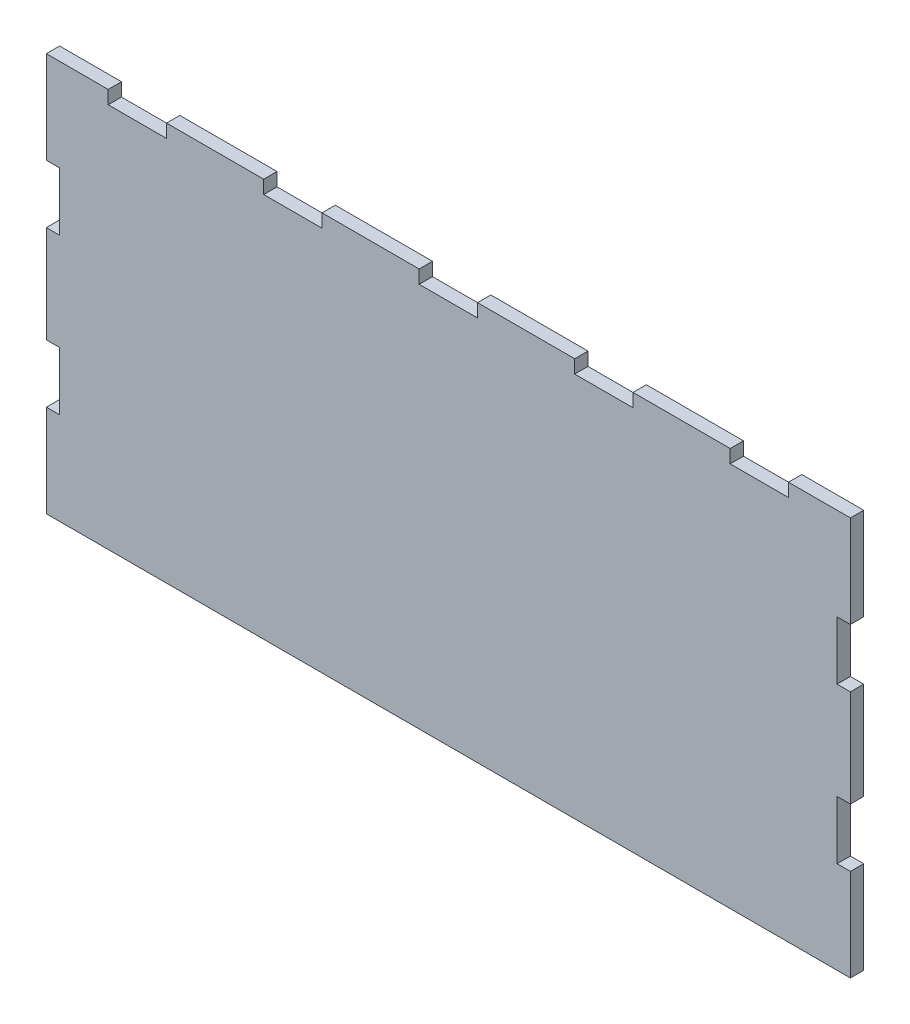
SolidWorks part; units mm, degrees
ref_plane "Front Plane" through (0, 0, 0) normal (0, 0, 1) x (1, 0, 0)
ref_plane "Top Plane" through (0, 0, 0) normal (0, 1, 0) x (1, 0, 0)
ref_plane "Right Plane" through (0, 0, 0) normal (1, 0, 0) x (0, 0, -1)
sketch "Sketch1" plane through (0, 0, 0) normal (0, 0, 1) x (1, 0, 0)
  line L1 (-131.3434, -65.0875) -> (131.3434, -65.0875)
  line L2 (-131.3434, -65.0875) -> (-131.3434, 65.0875)
  line L3 (-131.3434, 65.0875) -> (131.3434, 65.0875)
  line L4 (131.3434, -65.0875) -> (131.3434, 65.0875)
  line L5 (-131.3434, -65.0875) -> (131.3434, 65.0875) construction
  line L6 (-131.3434, 65.0875) -> (131.3434, -65.0875) construction
  point P0 (0, 0)
  dimension "D1" = 262.6868
  dimension "D2" = 130.175
extrude "Boss-Extrude1" add sketch "Sketch1" along normal blind 4.3434
sketch "Sketch2" plane through (0, 0, 4.3434) normal (0, 0, 1) x (1, 0, 0)
  line L2 (-60.325, 60.7441) -> (-41.275, 60.7441)
  line L3 (-60.325, 60.7441) -> (-60.325, 69.4309)
  line L4 (-60.325, 69.4309) -> (-41.275, 69.4309)
  line L5 (-41.275, 60.7441) -> (-41.275, 69.4309)
  line L6 (-60.325, 60.7441) -> (-41.275, 69.4309) construction
  line L7 (131.3434, 65.0875) -> (-131.3434, 65.0875) construction
  line L8 (-9.525, 60.7441) -> (9.525, 60.7441)
  line L9 (-9.525, 60.7441) -> (-9.525, 69.4309)
  line L10 (-9.525, 69.4309) -> (9.525, 69.4309)
  line L11 (9.525, 60.7441) -> (9.525, 69.4309)
  line L12 (-9.525, 60.7441) -> (9.525, 69.4309) construction
  line L13 (-9.525, 69.4309) -> (9.525, 60.7441) construction
  line L14 (41.275, 69.4309) -> (60.325, 69.4309)
  line L15 (60.325, 60.7441) -> (60.325, 69.4309)
  line L16 (41.275, 60.7441) -> (60.325, 60.7441)
  line L17 (41.275, 60.7441) -> (41.275, 69.4309)
  line L18 (92.075, 69.4309) -> (111.125, 69.4309)
  line L19 (111.125, 60.7441) -> (111.125, 69.4309)
  line L20 (92.075, 60.7441) -> (111.125, 60.7441)
  line L21 (92.075, 60.7441) -> (92.075, 69.4309)
  line L22 (-60.325, 69.4309) -> (-41.275, 60.7441) construction
  line L23 (-111.125, 60.7441) -> (-92.075, 60.7441)
  line L24 (-111.125, 60.7441) -> (-111.125, 69.4309)
  line L25 (-111.125, 69.4309) -> (-92.075, 69.4309)
  line L26 (-92.075, 60.7441) -> (-92.075, 69.4309)
  line L27 (-111.125, 60.7441) -> (-92.075, 69.4309) construction
  line L28 (-111.125, 69.4309) -> (-92.075, 60.7441) construction
  line L29 (-131.3434, 65.0875) -> (-131.3434, -65.0875) construction
  point P1 (-50.8, 65.0875)
  point P7 (0, 65.0875)
  point P15 (-101.6, 65.0875)
  point P32 (97.2566, 69.4309)
  dimension "D1" = 3
  dimension "D2" = 8.6868
  dimension "D3" = 19.05
  dimension "D4" = 121.8184
  dimension "D7" = 3
extrude "Cut-Extrude1" cut sketch "Sketch2" against normal through all
sketch "Sketch3" plane through (0, 0, 4.3434) normal (0, 0, 1) x (1, 0, 0)
  line L0 (-131.3434, 65.0875) -> (-131.3434, -65.0875) construction
  line L1 (-135.6868, -34.925) -> (-127, -34.925)
  line L2 (-135.6868, -34.925) -> (-135.6868, -15.875)
  line L3 (-135.6868, -15.875) -> (-127, -15.875)
  line L4 (-127, -34.925) -> (-127, -15.875)
  line L5 (-135.6868, -34.925) -> (-127, -15.875) construction
  line L6 (-135.6868, -15.875) -> (-127, -34.925) construction
  line L7 (-131.3434, -65.0875) -> (131.3434, -65.0875) construction
  line L9 (-135.6868, 34.925) -> (-127, 34.925)
  line L10 (-135.6868, 15.875) -> (-127, 15.875)
  line L11 (-127, 15.875) -> (-127, 34.925)
  line L12 (-135.6868, 15.875) -> (-135.6868, 34.925)
  point P0 (-131.3434, -25.4)
  dimension "D1" = 8.6868
  dimension "D2" = 39.6875
  dimension "D3" = 19.05
  dimension "D4" = 2
sketch "Sketch4" plane through (0, 0, 4.3434) normal (0, 0, 1) x (1, 0, 0)
  line L0 (0, -65.0875) -> (0, -7.9375) construction
  line L1 (-131.3434, -65.0875) -> (131.3434, -65.0875) construction
  line L2 (-19.05, -65.0875) -> (-19.05, -7.9375)
  line L3 (19.05, -65.0875) -> (19.05, -7.9375)
  arc A0 (-19.05, -65.0875) -> (19.05, -65.0875) centre (0, -65.0875) ccw
  arc A1 (19.05, -7.9375) -> (-19.05, -7.9375) centre (0, -7.9375) ccw
  point P5 (0, -36.5125)
  dimension "D1" = 38.1
  dimension "D2" = 57.15
extrude "Cut-Extrude2" [suppressed] cut sketch "Sketch4" against normal through all
extrude "Cut-Extrude3" cut sketch "Sketch3" against normal through all
mirror "Mirror1" about plane through (0, 0, 0) normal (1, 0, 0) of "Cut-Extrude3"
